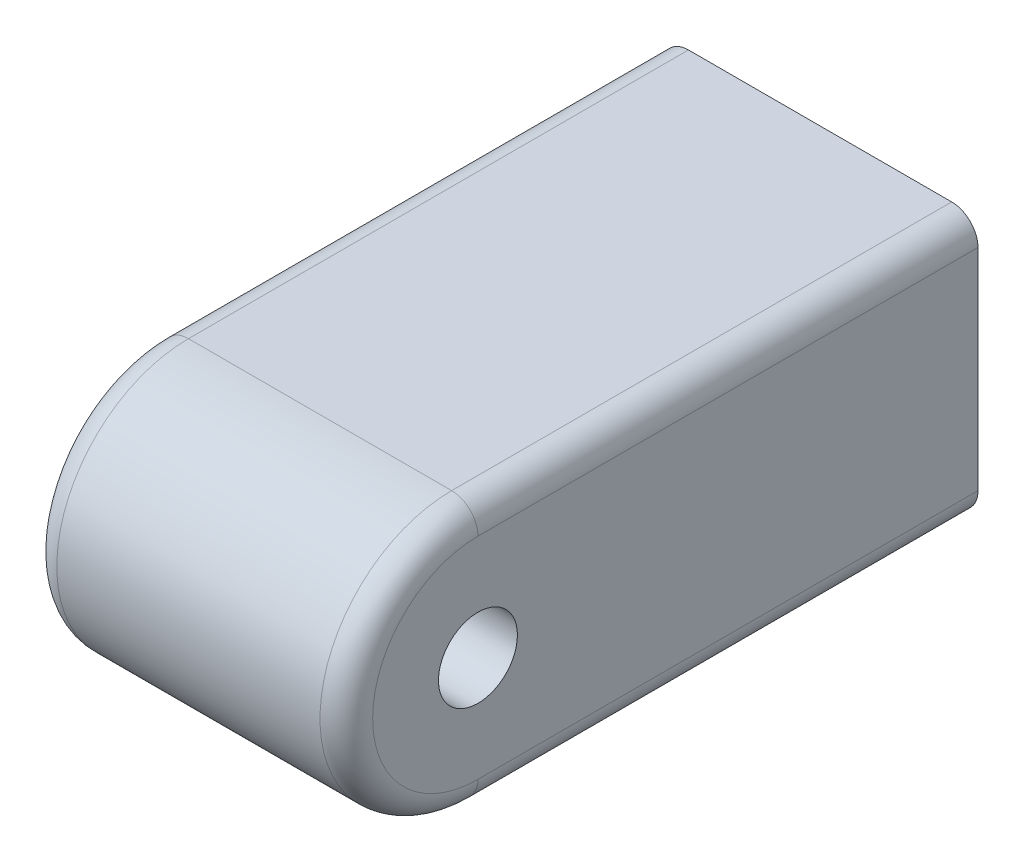
SolidWorks part; units mm, degrees
ref_plane "Front Plane" through (0, 0, 0) normal (0, 0, 1) x (1, 0, 0)
ref_plane "Top Plane" through (0, 0, 0) normal (0, 1, 0) x (1, 0, 0)
ref_plane "Right Plane" through (0, 0, 0) normal (1, 0, 0) x (0, 0, -1)
sketch "Sketch1" plane through (0, 0, 0) normal (1, 0, 0) x (0, 0, -1)
  line L0 (-35, 25) -> (60, 25)
  line L1 (60, 25) -> (60, -25)
  line L2 (60, -25) -> (-35, -25)
  line L3 (-92.4348, 0) -> (140.5823, 0) construction
  arc A0 (-35, 25) -> (-35, -25) centre (-35, 0) ccw
  point P5 (-60, 0)
  dimension "D3" = 60
  dimension "D1" = 120
  dimension "D2" = 50
extrude "Boss-Extrude1" add sketch "Sketch1" along normal blind 60
sketch "Sketch2" plane through (60, 0, 0) normal (1, 0, 0) x (0, 0, -1)
  line L0 (-61.8049, 0) -> (79.7059, 0) construction
  circle A0 centre (-35, 0) radius 7.5
  arc A1 (-35, 25) -> (-35, -25) centre (-35, 0) ccw construction
  dimension "D1" = 15
extrude "Cut-Extrude1" cut sketch "Sketch2" against normal up to next
sketch "Sketch3" plane through (0, 0, -60) normal (0, 0, -1) x (-1, 0, 0)
  line L0 (0, -25) -> (0, 25) construction
  line L1 (-60, 25) -> (0, 25) construction
  line L3 (-55, 20) -> (-5, 20)
  line L4 (-55, 20) -> (-55, -20)
  line L5 (-55, -20) -> (-5, -20)
  line L6 (-5, 20) -> (-5, -20)
  line L7 (-55, 20) -> (-5, -20) construction
  line L8 (-55, -20) -> (-5, 20) construction
  point P7 (-30, 0)
  dimension "D1" = 50
  dimension "D2" = 40
  dimension "D3" = 5
  dimension "D4" = 5
extrude "Cut-Extrude2" cut sketch "Sketch3" against normal blind 70
sketch "Sketch4" plane through (0, 0, -60) normal (0, 0, -1) x (-1, 0, 0)
  line L0 (-60, -25) -> (-60, 25) construction
  line L1 (-60, 25) -> (0, 25) construction
  line L2 (-60, -25) -> (0, -25) construction
  line L3 (0, -25) -> (0, 25) construction
  line L5 (-83.0378, 0) -> (21.6951, 0) construction
  line L6 (-60, -25) -> (-60, 25) construction
  circle A0 centre (-50, 22.5) radius 1.5
  circle A1 centre (-50, -22.5) radius 1.5
  circle A2 centre (-10, -22.5) radius 1.5
  circle A3 centre (-10, 22.5) radius 1.5
  circle A6 centre (-57.5, 0) radius 1.5
  circle A7 centre (-2.5, 0) radius 1.5
  dimension "D1" = 3
  dimension "D2" = 10
  dimension "D3" = 2.5
  dimension "D4" = 2.5
  dimension "D5" = 2.5
  dimension "D6" = 10
  dimension "D7" = 2.5
extrude "Cut-Extrude3" cut sketch "Sketch4" against normal blind 10
fillet "Fillet2" radius 5 6 edges at (0, -25, -12.5) (0, 0, 60) (60, -25, -12.5) (60, 0, 60) (0, 25, -12.5) (60, 25, -12.5)
